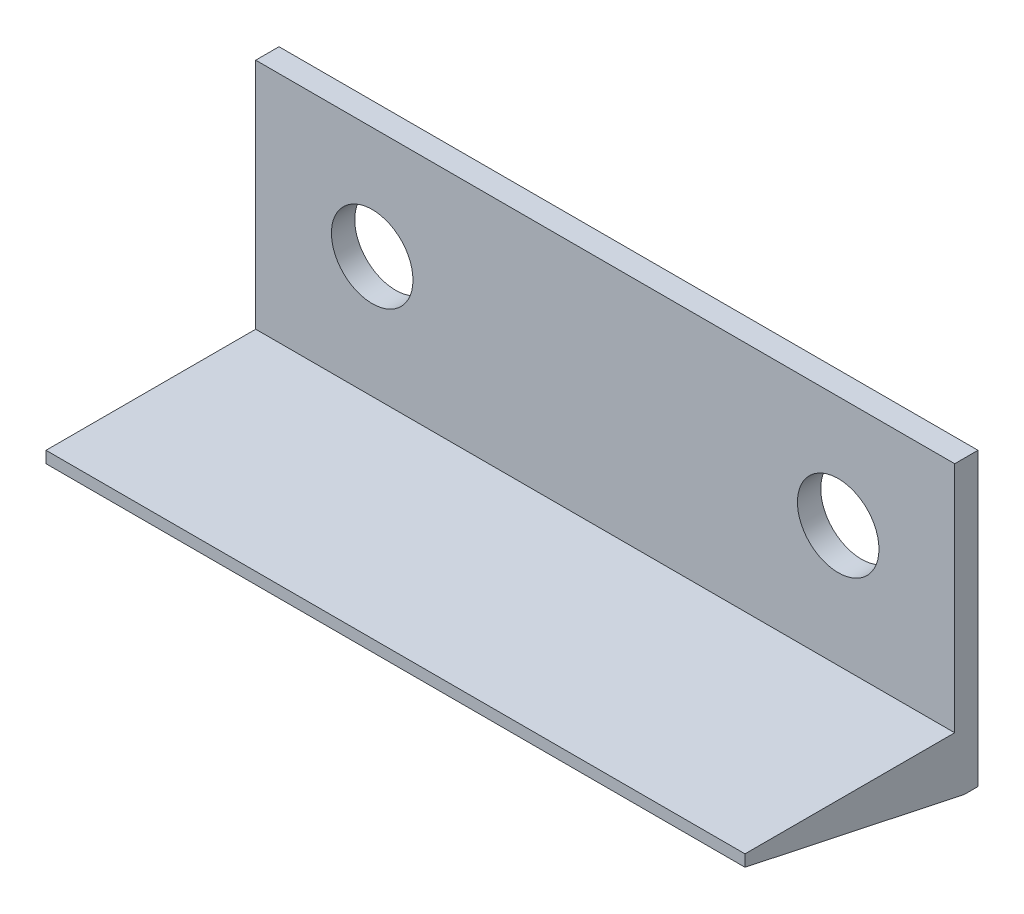
SolidWorks part; units mm, degrees
ref_plane "Front Plane" through (0, 0, 0) normal (0, 0, 1) x (1, 0, 0)
ref_plane "Top Plane" through (0, 0, 0) normal (0, 1, 0) x (1, 0, 0)
ref_plane "Right Plane" through (0, 0, 0) normal (1, 0, 0) x (0, 0, -1)
sketch "Sketch1" plane through (0, 0, 0) normal (0, 0, 1) x (1, 0, 0)
  line L0 (-10, 0.2) -> (10, 0.2) construction
  line L1 (-15, 5) -> (15, 5)
  line L2 (-15, 5) -> (-15, -5)
  line L3 (-15, -5) -> (15, -5)
  line L4 (15, 5) -> (15, -5)
  line L5 (-15, 5) -> (15, -5) construction
  line L6 (-15, -5) -> (15, 5) construction
  line L7 (0, 0) -> (0, 0.2) construction
  circle A0 centre (-10, 0.2) radius 1.75
  circle A1 centre (10, 0.2) radius 1.75
  point P0 (0, 0)
  dimension "D3" = 3.5
  dimension "D1" = 10
  dimension "D2" = 30
  dimension "D4" = 5.2
  dimension "D5" = 20
extrude "Boss-Extrude1" add sketch "Sketch1" along normal blind 1
sketch "Sketch2" plane through (0, 0, 0) normal (0, 0, 1) x (1, 0, 0)
  line L0 (15, -5) -> (15, 5) construction
  line L1 (-15, -5) -> (15, -5)
  line L2 (-15, -5) -> (-15, -7.5)
  line L3 (-15, -7.5) -> (15, -7.5)
  line L4 (15, -5) -> (15, -7.5)
  dimension "D1" = 2.5
extrude "Boss-Extrude2" add sketch "Sketch2" along normal blind 10
chamfer "Chamfer1" distance 2 angle 78 1 edges at (0, -7.5, 10)
